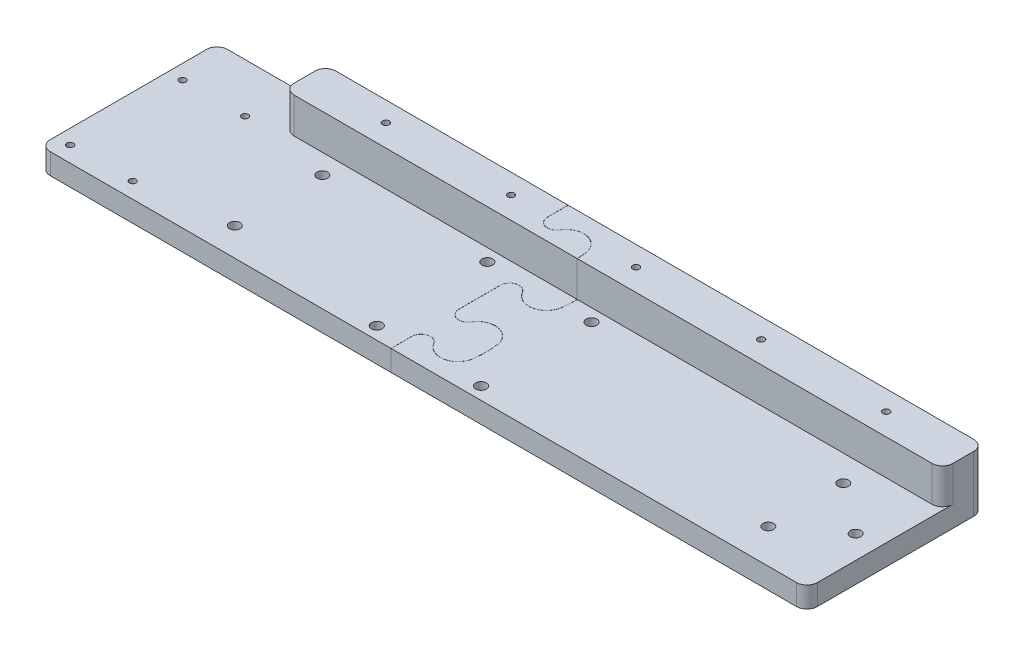
SolidWorks part; units mm, degrees
other "MotorEnd"
other "FlangeEnd"
ref_plane "Front Plane" through (0, 0, 0) normal (0, 0, 1) x (1, 0, 0)
ref_plane "Top Plane" through (0, 0, 0) normal (0, 1, 0) x (1, 0, 0)
ref_plane "Right Plane" through (0, 0, 0) normal (1, 0, 0) x (0, 0, -1)
sketch "Sketch1" plane through (0, 0, 0) normal (0, 1, 0) x (1, 0, 0)
  line L1 (0, 0) -> (368, 0)
  line L2 (0, 0) -> (0, 85)
  line L3 (0, 85) -> (368, 85)
  line L4 (368, 0) -> (368, 85)
  dimension "D1" = 368
  dimension "D2" = 85
extrude "Boss-Extrude1" add sketch "Sketch1" along normal blind 6
sketch "Sketch2" plane through (0, 6, 0) normal (0, 1, 0) x (1, 0, 0)
  line L0 (368, 0) -> (368, 85) construction
  line L1 (52, 85) -> (368, 85)
  line L2 (52, 85) -> (52, 65)
  line L3 (52, 65) -> (368, 65)
  line L4 (368, 85) -> (368, 65)
  dimension "D1" = 316
  dimension "D2" = 20
extrude "Boss-Extrude3" add sketch "Sketch2" along normal blind 17 contours L1 L4 L3 L2
sketch "Sketch3" plane through (0, 6, 0) normal (0, 1, 0) x (1, 0, 0)
  line L0 (52, 85) -> (0, 85) construction
  line L1 (0, 85) -> (0, 0) construction
  line L2 (7, 7.55) -> (37, 7.55) construction
  line L3 (37, 7.55) -> (37, 61.45) construction
  line L4 (37, 61.45) -> (7, 61.45) construction
  line L5 (7, 61.45) -> (7, 7.55) construction
  line L6 (80, 13.5) -> (80, 55.5) construction
  line L7 (332.9511, 52.4871) -> (332.9511, 16.5232) construction
  line L8 (332.9511, 34.5051) -> (356.8481, 34.5051) construction
  line L9 (52, 85) -> (368, 85) construction
  line L10 (90.5, 75.5) -> (150.5, 75.5) construction
  line L11 (150.5, 75.5) -> (210.5, 75.5) construction
  line L12 (210.5, 75.5) -> (270.5, 75.5) construction
  line L13 (270.5, 75.5) -> (330.5, 75.5) construction
  circle A0 centre (7, 61.45) radius 1.575
  circle A1 centre (7, 7.55) radius 1.575
  circle A2 centre (37, 7.55) radius 1.575
  circle A3 centre (37, 61.45) radius 1.575
  circle A4 centre (80, 55.5) radius 2.55
  circle A5 centre (80, 13.5) radius 2.55
  circle A6 centre (332.9511, 52.4871) radius 2.55
  circle A7 centre (356.8481, 34.5051) radius 2.55
  circle A8 centre (332.9511, 16.5232) radius 2.55
  circle A9 centre (90.5, 75.5) radius 1.6
  circle A10 centre (150.5, 75.5) radius 1.6
  circle A11 centre (210.5, 75.5) radius 1.6
  circle A12 centre (270.5, 75.5) radius 1.6
  circle A13 centre (330.5, 75.5) radius 1.6
  dimension "D1" = 3.15
  dimension "D6" = 5.1
  dimension "D8" = 5.1
  dimension "D13" = 3.2
  dimension "D2" = 23.55
  dimension "D3" = 53.9
  dimension "D4" = 30
  dimension "D5" = 7
  dimension "D7" = 42
  dimension "D9" = 80
  dimension "D10" = 332.9511
  dimension "D11" = 35.9639
  dimension "D12" = 23.8969
  dimension "D14" = 60
  dimension "D15" = 60
  dimension "D16" = 60
  dimension "D17" = 60
  dimension "D18" = 9.5
  dimension "D19" = 90.5
  dimension "D20" = 32.5129
  dimension "D21" = 29.5
extrude "Cut-Extrude1" cut sketch "Sketch3" against normal through all both and the other way through all contours A9
sketch "Sketch4" plane through (0, 0, 0) normal (0, -1, 0) x (1, 0, 0)
  line L4 (0, 0) -> (0, -85)
  line L5 (0, -85) -> (368, -85)
  line L6 (368, -85) -> (368, 0)
  line L7 (368, 0) -> (0, 0)
  line L8 (0, 0) -> (0, -85)
  line L9 (0, -85) -> (368, -85)
  line L10 (368, -85) -> (368, 0)
  line L11 (368, 0) -> (0, 0)
  circle A0 centre (7, -7.55) radius 3.575
  circle A1 centre (37, -7.55) radius 3.575
  circle A2 centre (80, -13.5) radius 5.075
  circle A3 centre (80, -55.5) radius 5.075
  circle A4 centre (37, -61.45) radius 3.575
  circle A5 centre (7, -61.45) radius 3.575
  circle A6 centre (90.5, -75.5) radius 3.575
  circle A7 centre (150.5, -75.5) radius 3.575
  circle A8 centre (210.5, -75.5) radius 3.575
  circle A9 centre (270.5, -75.5) radius 3.575
  circle A10 centre (330.5, -75.5) radius 3.575
  circle A11 centre (332.9511, -52.4871) radius 5.075
  circle A12 centre (356.8481, -34.5051) radius 5.075
  circle A13 centre (332.9511, -16.5232) radius 5.075
  dimension "D1" = 7.15
  dimension "D2" = 7.15
  dimension "D3" = 10.15
  dimension "D4" = 0
extrude "Boss-Extrude4" add sketch "Sketch4" along normal blind 4
fillet "Fillet1" radius 5 7 edges at (368, 9.5, -85) (368, 14.5, -65) (368, 1, 0) (52, 14.5, -85) (52, 14.5, -65) (0, 1, 0) (0, 1, -85)
sketch "Sketch7" plane through (0, -4, 0) normal (0, -1, 0) x (1, 0, 0)
  line L0 (192.7645, -21.25) -> (192.7645, -35.1728) construction
  line L1 (363, 0) -> (5, 0) construction
  line L2 (0, -42.5) -> (368, -42.5) construction
  line L3 (0, -5) -> (0, -80) construction
  line L4 (368, -80) -> (368, -5) construction
  line L5 (149.6901, -42.5) -> (149.6901, 0) construction
  line L6 (149.6901, -21.25) -> (215.9921, -21.25) construction
  line L7 (168.4297, -9.9687) -> (168.4297, 0)
  line L8 (168.4297, -32.5313) -> (168.4297, -52.4687)
  line L9 (192.7645, -63.75) -> (192.7645, -49.8272) construction
  line L10 (168.4297, -75.0313) -> (168.4297, -85)
  line L11 (168.4797, -75.0313) -> (168.4797, -85)
  line L12 (168.4797, -32.5313) -> (168.4797, -52.4687)
  line L13 (168.4797, -9.9687) -> (168.4797, 0)
  line L14 (168.4297, -85) -> (168.4797, -85)
  line L15 (168.4297, 0) -> (168.4797, 0)
  arc A0 (192.4091, -26.9917) -> (192.4091, -15.5083) centre (146.212, -21.25) ccw
  arc A1 (192.4091, -15.5083) -> (176.7645, -12.25) centre (184.0306, -16.5496) ccw
  arc A2 (176.7645, -12.25) -> (168.4297, -9.9687) centre (172.9093, -9.9687) cw
  arc A3 (176.7645, -30.25) -> (168.4297, -32.5313) centre (172.9093, -32.5313) ccw
  arc A4 (192.4091, -26.9917) -> (176.7645, -30.25) centre (184.0306, -25.9504) cw
  arc A5 (192.4091, -58.0083) -> (176.7645, -54.75) centre (184.0306, -59.0496) ccw
  arc A6 (176.7645, -54.75) -> (168.4297, -52.4687) centre (172.9093, -52.4687) cw
  arc A7 (176.7645, -72.75) -> (168.4297, -75.0313) centre (172.9093, -75.0313) ccw
  arc A8 (192.4091, -69.4917) -> (176.7645, -72.75) centre (184.0306, -68.4504) cw
  arc A9 (192.4091, -58.0083) -> (192.4091, -69.4917) centre (146.212, -63.75) cw
  arc A10 (176.7215, -72.7755) -> (168.4797, -75.0313) centre (172.9093, -75.0313) ccw
  arc A11 (192.4587, -69.4979) -> (176.7215, -72.7755) centre (184.0306, -68.4504) cw
  arc A12 (192.4587, -58.0021) -> (192.4587, -69.4979) centre (146.212, -63.75) cw
  arc A13 (192.4587, -58.0021) -> (176.7215, -54.7245) centre (184.0306, -59.0496) ccw
  arc A14 (176.7215, -54.7245) -> (168.4797, -52.4687) centre (172.9093, -52.4687) cw
  arc A15 (176.7215, -30.2755) -> (168.4797, -32.5313) centre (172.9093, -32.5313) ccw
  arc A16 (192.4587, -26.9979) -> (176.7215, -30.2755) centre (184.0306, -25.9504) cw
  arc A17 (192.4587, -26.9979) -> (192.4587, -15.5021) centre (146.212, -21.25) ccw
  arc A18 (192.4587, -15.5021) -> (176.7215, -12.2245) centre (184.0306, -16.5496) ccw
  arc A19 (176.7215, -12.2245) -> (168.4797, -9.9687) centre (172.9093, -9.9687) cw
  point P40 (168.4297, -42.5)
  dimension "D1" = 9
  dimension "D2" = 16
  dimension "D3" = 0.05
extrude "Weird Cut" cut sketch "Sketch7" against normal through all both and the other way through all
sketch "Sketch8" plane through (0, 6, 0) normal (0, 1, 0) x (1, 0, 0)
  line L0 (155.6471, 59) -> (205.6471, 59) construction
  line L1 (155.6471, 6) -> (205.6471, 6) construction
  line L2 (155.6471, 59) -> (155.6471, 6) construction
  line L3 (205.6471, 6) -> (205.6471, 59) construction
  line L4 (192.8145, 21.25) -> (168.4797, 21.25) construction
  line L5 (168.4797, 21.25) -> (168.4797, 42.5) construction
  line L6 (168.4797, 52.4687) -> (168.4797, 32.5313) construction
  line L7 (180.6471, 21.25) -> (180.6471, 59) construction
  line L8 (192.7978, 65) -> (363, 65) construction
  line L9 (168.4797, 0) -> (363, 0) construction
  circle A0 centre (205.6471, 59) radius 2.575
  circle A1 centre (155.6471, 59) radius 2.575
  arc A2 (192.4587, 15.5021) -> (192.4587, 26.9979) centre (146.212, 21.25) ccw construction
  circle A3 centre (205.6471, 6) radius 2.575
  circle A4 centre (155.6471, 6) radius 2.575
  point P12 (180.6471, 21.25)
  point P16 (180.6471, 59)
  dimension "D4" = 5.15
  dimension "D1" = 50
  dimension "D2" = 6
  dimension "D3" = 6
extrude "If you no stay i make u stai breh" cut sketch "Sketch8" against normal through all both and the other way through all
sketch "Sketch9" plane through (0, -4, 0) normal (0, -1, 0) x (1, 0, 0)
  circle A0 centre (155.6471, -6) radius 5.075
  circle A1 centre (205.6471, -6) radius 5.075
  circle A2 centre (205.6471, -59) radius 5.075
  circle A3 centre (155.6471, -59) radius 5.075
  dimension "D1" = 10.15
extrude "yuh" cut sketch "Sketch9" against normal blind 4 and the other way through all
other "Save Bodies1"
